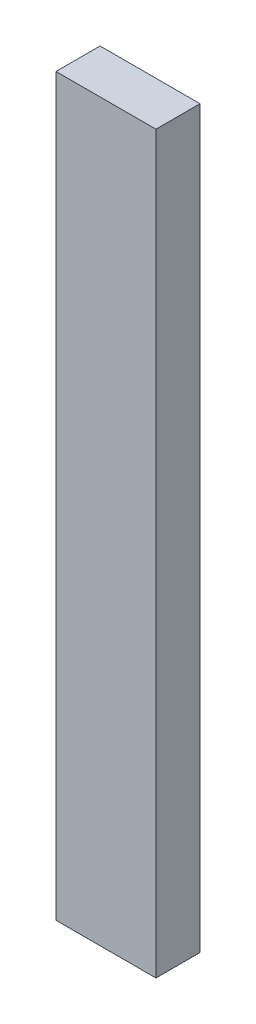
SolidWorks part; units mm, degrees
ref_plane "Front Plane" through (0, 0, 0) normal (0, 0, 1) x (1, 0, 0)
ref_plane "Top Plane" through (0, 0, 0) normal (0, 1, 0) x (1, 0, 0)
ref_plane "Right Plane" through (0, 0, 0) normal (1, 0, 0) x (0, 0, -1)
sketch "Sketch1" plane through (0, 0, 0) normal (0, 0, 1) x (1, 0, 0)
  line L1 (-1.7, 12.5) -> (1.7, 12.5)
  line L2 (-1.7, 12.5) -> (-1.7, -12.5)
  line L3 (-1.7, -12.5) -> (1.7, -12.5)
  line L4 (1.7, 12.5) -> (1.7, -12.5)
  line L5 (-1.7, 12.5) -> (1.7, -12.5) construction
  line L6 (-1.7, -12.5) -> (1.7, 12.5) construction
  point P0 (0, 0)
  dimension "D1" = 25
  dimension "D2" = 3.4
extrude "Boss-Extrude1" add sketch "Sketch1" along normal blind 1.5
